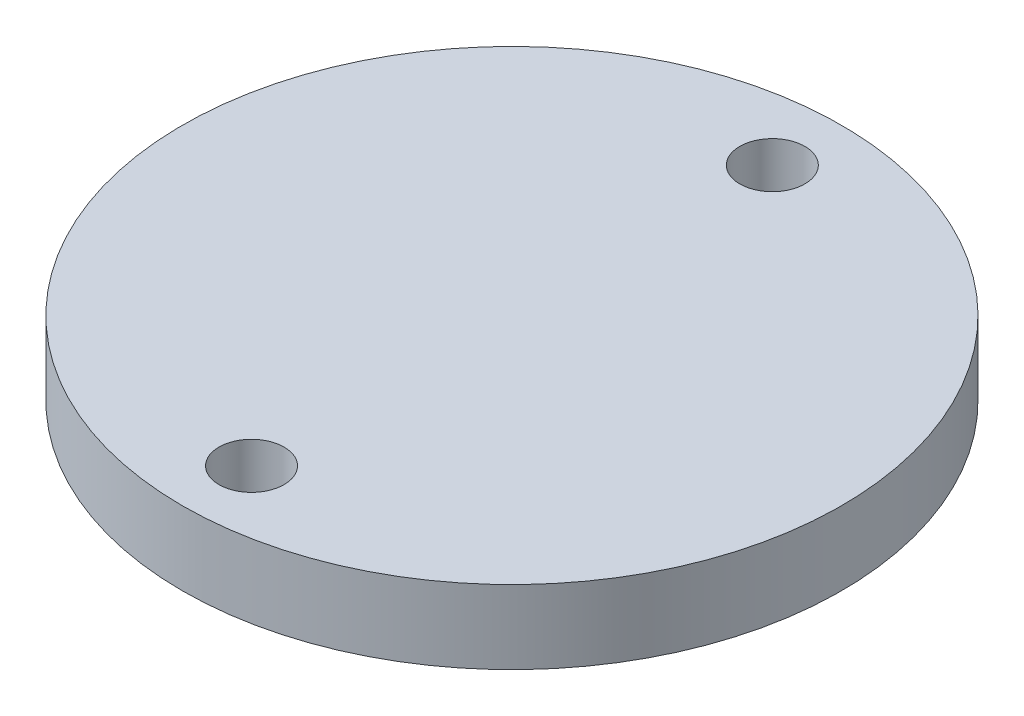
SolidWorks part; units mm, degrees
ref_plane "Front Plane" through (0, 0, 0) normal (0, 0, 1) x (1, 0, 0)
ref_plane "Top Plane" through (0, 0, 0) normal (0, 1, 0) x (1, 0, 0)
ref_plane "Right Plane" through (0, 0, 0) normal (1, 0, 0) x (0, 0, -1)
sketch "Sketch1" plane through (0, 0, 0) normal (0, 1, 0) x (1, 0, 0)
  circle A0 centre (0, 0) radius 10.287
  dimension "D1" = 20.574
extrude "Boss-Extrude1" add sketch "Sketch1" along normal blind 2.3
sketch "Sketch2" plane through (0, 0, 0) normal (0, -1, 0) x (-1, 0, 0)
  circle A0 centre (0, 0) radius 4.4
  dimension "D1" = 8.8
extrude "Boss-Extrude2" add sketch "Sketch2" along normal blind 3.3
sketch "Sketch4" plane through (0, 0, 0) normal (0, 1, 0) x (1, 0, 0)
  circle A0 centre (0, 8.128) radius 1.016
  circle A1 centre (0, -8.128) radius 1.016
  dimension "D1" = 2.032
  dimension "D2" = 2.032
  dimension "D3" = 8.128
  dimension "D4" = 8.128
  dimension "D5" = 16.256
extrude "Cut-Extrude1" cut sketch "Sketch4" along normal up to surface (2.3 mm away) up to face at (0, 2.3, 10.287)
